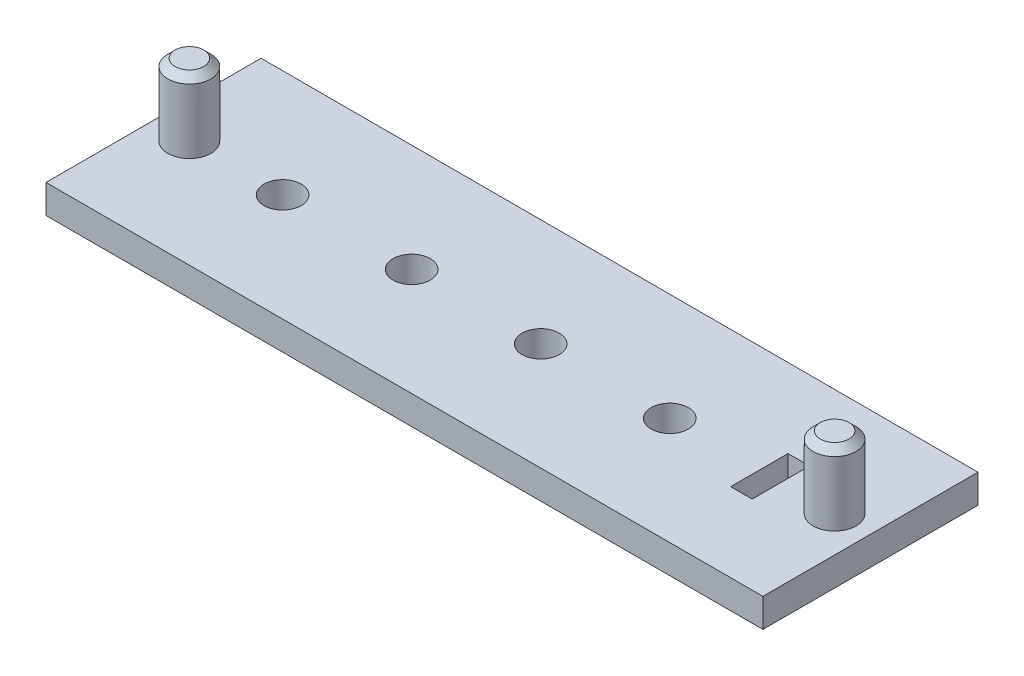
SolidWorks part; units mm, degrees
ref_plane "Alzado" through (0, 0, 0) normal (0, 0, 1) x (1, 0, 0)
ref_plane "Planta" through (0, 0, 0) normal (0, 1, 0) x (1, 0, 0)
ref_plane "Vista lateral" through (0, 0, 0) normal (1, 0, 0) x (0, 0, -1)
sketch "Croquis1" plane through (0, 0, 0) normal (0, 1, 0) x (1, 0, 0)
  line L0 (-25, 0) -> (25, 0) construction
  line L1 (-25, -7.5) -> (25, -7.5)
  line L2 (-25, -7.5) -> (-25, 7.5)
  line L3 (-25, 7.5) -> (25, 7.5)
  line L4 (25, -7.5) -> (25, 7.5)
  line L5 (-25, -7.5) -> (25, 7.5) construction
  line L6 (-25, 7.5) -> (25, -7.5) construction
  line L8 (17.25, -2) -> (18.75, -2)
  line L9 (17.25, -2) -> (17.25, 2)
  line L10 (17.25, 2) -> (18.75, 2)
  line L11 (18.75, -2) -> (18.75, 2)
  line L12 (17.25, -2) -> (18.75, 2) construction
  line L13 (17.25, 2) -> (18.75, -2) construction
  circle A0 centre (-16, 0) radius 1.3
  circle A1 centre (-7, 0) radius 1.3
  circle A2 centre (2, 0) radius 1.3
  circle A3 centre (11, 0) radius 1.3
  point P0 (0, 0)
  point P10 (18, 0)
  dimension "D3" = 2.6
  dimension "D7" = 7
  dimension "D1" = 50
  dimension "D2" = 15
  dimension "D4" = 9
  dimension "D6" = 9
  dimension "D8" = 4
  dimension "D9" = 1.5
  dimension "D10" = 7
  dimension "D5" = 4
extrude "Saliente-Extruir1" add sketch "Croquis1" along normal blind 2
sketch "Croquis2" plane through (0, 2, 0) normal (0, 1, 0) x (1, 0, 0)
  line L0 (-25, 0) -> (25, 0) construction
  line L1 (-25, 7.5) -> (-25, -7.5) construction
  line L2 (25, -7.5) -> (25, 7.5) construction
  circle A0 centre (-22.5, 0) radius 1.5
  circle A1 centre (22.5, 0) radius 1.5
  dimension "D1" = 3
  dimension "D3" = 3
  dimension "D2" = 2.5
  dimension "D4" = 2.5
extrude "Saliente-Extruir2" add sketch "Croquis2" along normal blind 5
cosmetic thread "Rosca cosmética1" parameters "D2"=2
cosmetic thread "Rosca cosmética2" parameters "D2"=2
chamfer "Chaflán1" distance 0.5 angle 45 1 edges at (-22.5, 7, 1.5)
chamfer "Chaflán2" distance 0.5 angle 45 1 edges at (22.5, 7, 1.5)
